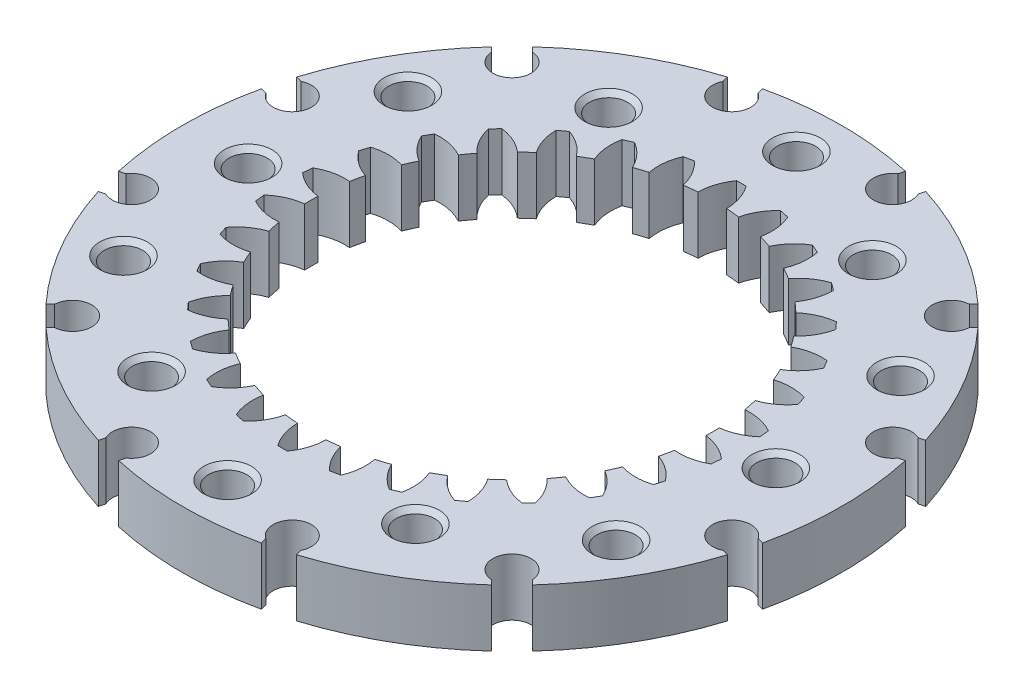
SolidWorks part; units mm, degrees
ref_plane "前视基准面" through (0, 0, 0) normal (0, 0, 1) x (1, 0, 0)
ref_plane "上视基准面" through (0, 0, 0) normal (0, 1, 0) x (1, 0, 0)
ref_plane "右视基准面" through (0, 0, 0) normal (1, 0, 0) x (0, 0, -1)
sketch "草图1" plane through (0, 0, 0) normal (0, 1, 0) x (1, 0, 0)
  circle A0 centre (0, 0) radius 34.5
  dimension "D1" = 69
extrude "凸台-拉伸1" add sketch "草图1" along normal blind 6
sketch "草图2" plane through (0, 6, 0) normal (0, 1, 0) x (1, 0, 0)
  circle A0 centre (0, 0) radius 21
  dimension "D1" = 42
extrude "切除-拉伸1" cut sketch "草图2" against normal blind 6
sketch "草图3" plane through (0, 6, 0) normal (0, 1, 0) x (1, 0, 0)
  line L0 (0, 21) -> (0, 24) construction
  line L1 (0, 21) -> (-1.5, 21) construction
  line L2 (0, 22.5) -> (-1.25, 22.5) construction
  line L3 (0.5, 24) -> (-0.5, 24)
  arc A0 (1.501, 20.9463) -> (-1.501, 20.9463) centre (0, 0) ccw
  arc A1 (-0.5, 24) -> (-1.501, 20.9463) centre (3.875, 20.875) ccw
  arc A2 (0.5, 24) -> (1.501, 20.9463) centre (-3.875, 20.875) cw
  dimension "D1" = 42
  dimension "D2" = 0.5
  dimension "D3" = 1.25
  dimension "D4" = 1.5
  dimension "D5" = 3
extrude "切除-拉伸2" cut sketch "草图3" against normal blind 6
pattern_circular "阵列(圆周)1" count 30 over 360 about axis through (0, 0, 0) along (0, 1, 0) of "切除-拉伸2"
sketch "草图4" plane through (0, 6, 0) normal (0, 1, 0) x (1, 0, 0)
  line L0 (0, 0) -> (0, 29.75) construction
  circle A0 centre (0, 29.75) radius 2
  dimension "D2" = 4
  dimension "D1" = 29.75
extrude "切除-拉伸3" cut sketch "草图4" against normal blind 6
chamfer "倒角1" distance 0.5 angle 45 2 edges at (0, 0, -27.75) (0, 6, -27.75)
pattern_circular "阵列(圆周)2" count 6 over 360 about axis through (0, 0, 0) along (0, 1, 0) of "切除-拉伸3", "倒角1"
sketch "草图5" plane through (0, 6, 0) normal (0, 1, 0) x (1, 0, 0)
  line L0 (-10.2185, 21.7217) -> (-13.7023, 19.7103) construction
  line L1 (-11.9604, 20.716) -> (0, 0) construction
  line L2 (-11.9604, 20.716) -> (-13.8, 23.9023) construction
  circle A0 centre (-13.8, 23.9023) radius 2
  dimension "D3" = 4
  dimension "D1" = 180
  dimension "D2" = 27.6
extrude "切除-拉伸4" cut sketch "草图5" against normal blind 6
chamfer "倒角2" distance 0.5 angle 45 2 edges at (-13.8, 0, -21.9023) (-13.8, 6, -21.9023)
pattern_circular "阵列(圆周)3" count 6 over 360 about axis through (0, 0, 0) along (0, 1, 0) of "切除-拉伸4", "倒角2"
sketch "草图6" plane through (0, 6, 0) normal (0, 1, 0) x (1, 0, 0)
  line L0 (0, 0) -> (0, 29.75) construction
  line L1 (0, 0) -> (-8.4116, 31.3926) construction
  line L3 (-7.3051, 33.0586) -> (-7.7392, 34.6786)
  line L4 (-10.2029, 32.2822) -> (-10.637, 33.9021)
  line L5 (-10.637, 33.9021) -> (-7.7392, 34.6786)
  arc A0 (-10.2029, 32.2822) -> (-7.3051, 33.0586) centre (-8.4116, 31.3926) ccw
  dimension "D3" = 4
  dimension "D1" = 15
  dimension "D2" = 32.5
extrude "切除-拉伸5" cut sketch "草图6" against normal blind 6
pattern_circular "阵列(圆周)4" count 12 over 360 about axis through (0, 0, 0) along (0, 1, 0) of "切除-拉伸5"
